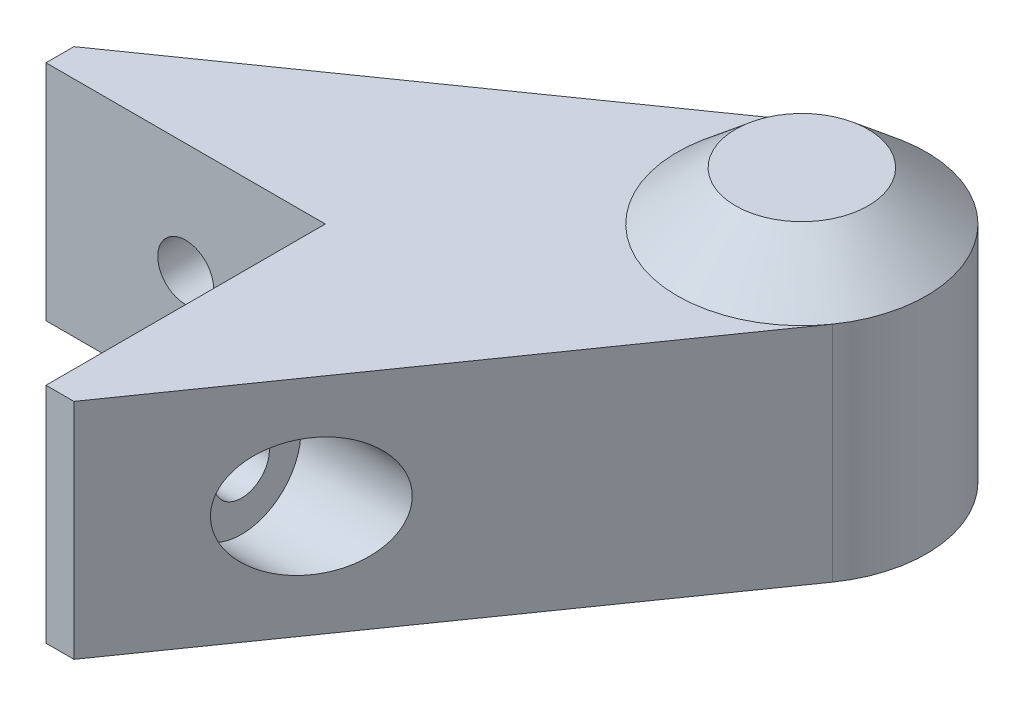
SolidWorks part; units mm, degrees
ref_plane "Front Plane" through (0, 0, 0) normal (0, 0, 1) x (1, 0, 0)
ref_plane "Top Plane" through (0, 0, 0) normal (0, 1, 0) x (1, 0, 0)
ref_plane "Right Plane" through (0, 0, 0) normal (1, 0, 0) x (0, 0, -1)
sketch "Sketch1" plane through (0, 0, 0) normal (0, 1, 0) x (1, 0, 0)
  line L1 (10, -10) -> (-10, -10) construction
  line L2 (10, -10) -> (10, 10) construction
  line L3 (10, 10) -> (-10, 10) construction
  line L4 (-10, -10) -> (-10, 10) construction
  line L5 (10, -10) -> (-10, 10) construction
  line L6 (10, 10) -> (-10, -10) construction
  line L8 (-10, 10) -> (10, 10)
  line L9 (10, 10) -> (10, -10)
  line L10 (-10, 10) -> (-10, 12)
  line L11 (-10, 12) -> (21.9469, 34.3695)
  line L12 (10, -10) -> (12, -10)
  line L13 (34.3695, 21.9469) -> (12, -10)
  arc A0 (21.9469, 34.3695) -> (34.3695, 21.9469) centre (27.063, 27.063) cw
  point P0 (0, 0)
  point P1 (16.2909, 16.2861)
  point P12 (4.1421, 26.1421)
  point P13 (36.5207, 14.5207)
  dimension "D3" = 35
  dimension "D1" = 20
  dimension "D2" = 2
  dimension "D4" = 39
  dimension "D5" = 35
extrude "Boss-Extrude1" add sketch "Sketch1" against normal blind 16
sketch "Sketch10" plane through (0, 0, 0) normal (0, 1, 0) x (1, 0, 0)
  circle A0 centre (27.063, 27.063) radius 8.9196
  arc A1 (34.3695, 21.9469) -> (21.9469, 34.3695) centre (27.063, 27.063) ccw construction
extrude "Boss-Extrude8" add sketch "Sketch10" along normal blind 3.5 draft 50
sketch "Sketch12" plane through (10, 0, 0) normal (-1, 0, 0) x (0, 0, 1)
  line L0 (0, 0) -> (0, -16) construction
  line L1 (-10, 0) -> (10, 0) construction
  line L2 (-10, -16) -> (10, -16) construction
  circle A0 centre (0, -8) radius 2
  point P8 (0, -8)
  dimension "D1" = 4
extrude "Cut-Extrude3" cut sketch "Sketch12" against normal through all
sketch "Sketch13" plane through (10, 0, 0) normal (-1, 0, 0) x (0, 0, 1)
  circle A0 centre (0, -8) radius 4.25
  dimension "D1" = 8.5
extrude "Cut-Extrude4" cut sketch "Sketch13" against normal through all from offset 4 offset against normal yes
ref_plane "Plane4" through (0, 0, 0) normal (-0.7071, 0, -0.7071) x (-0.7071, 0, 0.7071)
mirror "Mirror3" about plane through (0, 0, 0) normal (-0.7071, 0, -0.7071) of "Cut-Extrude3", "Cut-Extrude4"
